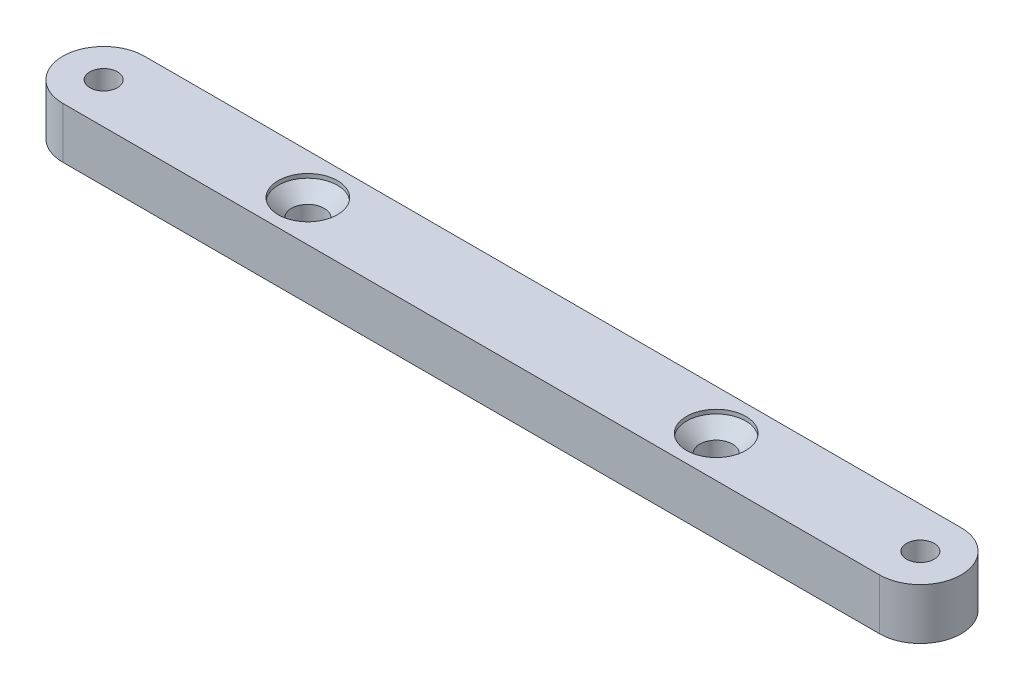
SolidWorks part; units mm, degrees
material "PET"
ref_plane "Plan de face" through (0, 0, 0) normal (0, 0, 1) x (1, 0, 0)
ref_plane "Plan de dessus" through (0, 0, 0) normal (0, 1, 0) x (1, 0, 0)
ref_plane "Plan de droite" through (0, 0, 0) normal (1, 0, 0) x (0, 0, -1)
sketch "Esquisse1" plane through (0, 0, 0) normal (0, 1, 0) x (1, 0, 0)
  line L0 (0, 4) -> (0, -4) construction
  line L1 (-44, 0) -> (44, 0) construction
  line L2 (40, 0) -> (-40, 0) construction
  line L3 (40, -4) -> (-40, -4)
  line L4 (40, 4) -> (-40, 4)
  arc A0 (40, -4) -> (40, 4) centre (40, 0) ccw
  arc A1 (-40, 4) -> (-40, -4) centre (-40, 0) ccw
  circle A2 centre (-40, 0) radius 1.35
  circle A3 centre (40, 0) radius 1.35
  point P7 (0, 0)
  point P16 (-49, 0)
  point P17 (49, 0)
  point P18 (0, 4)
  point P19 (0, -3.7372)
  point P20 (0, -4)
  dimension "D3" = 2.7
  dimension "D1" = 8
  dimension "D2" = 80
extrude "Boss.-Extru.1" add sketch "Esquisse1" along normal blind 5
hole_wizard "Fraisage pour vis à tête fraisée M31" positions "Esquisse3" profile "Esquisse2" countersink size "M3" standard "Ansi Metric" end condition through all
sketch "Esquisse3" plane through (0, 5, 0) normal (0, 1, 0) x (1, 0, 0)
  line L0 (0, -55) -> (0, 55) construction
  point P0 (-20, 0)
  dimension "D1" = 20
sketch "Esquisse2" plane through (-20, 5, 0) normal (1, 0, 0) x (0, 0, 1)
  line L0 (0, 0) -> (0, 5)
  line L1 (0, 5) -> (1.6, 5)
  line L2 (1.6, 5) -> (1.6, 1.7)
  line L3 (1.6, 1.7) -> (2.9, 0.4)
  line L4 (2.9, 0.4) -> (2.9, 0)
  line L6 (2.9, 0) -> (0, 0)
  line L7 (-1.6, 1.7) -> (-2.9, 0.4) construction
  line L11 (0, -6.35) -> (0, 107.95) construction
  dimension "Diamètre du perçage jusqu'au prochain" = 3.2
  dimension "Profondeur du perçage jusqu'au prochain" = 5
  dimension "Diamètre du fraisage" = 5.8
  dimension "Angle du fraisage" = 90
  dimension "Dégagement de la tête" = 0.4
mirror "Symétrie1" about plane through (0, 0, 0) normal (1, 0, 0) of "Fraisage pour vis à tête fraisée M31"
sketch "Esquisse4" plane through (0, 5, 0) normal (0, 1, 0) x (1, 0, 0)
  point P0 (40, 0)
  point P1 (-40, 0)
